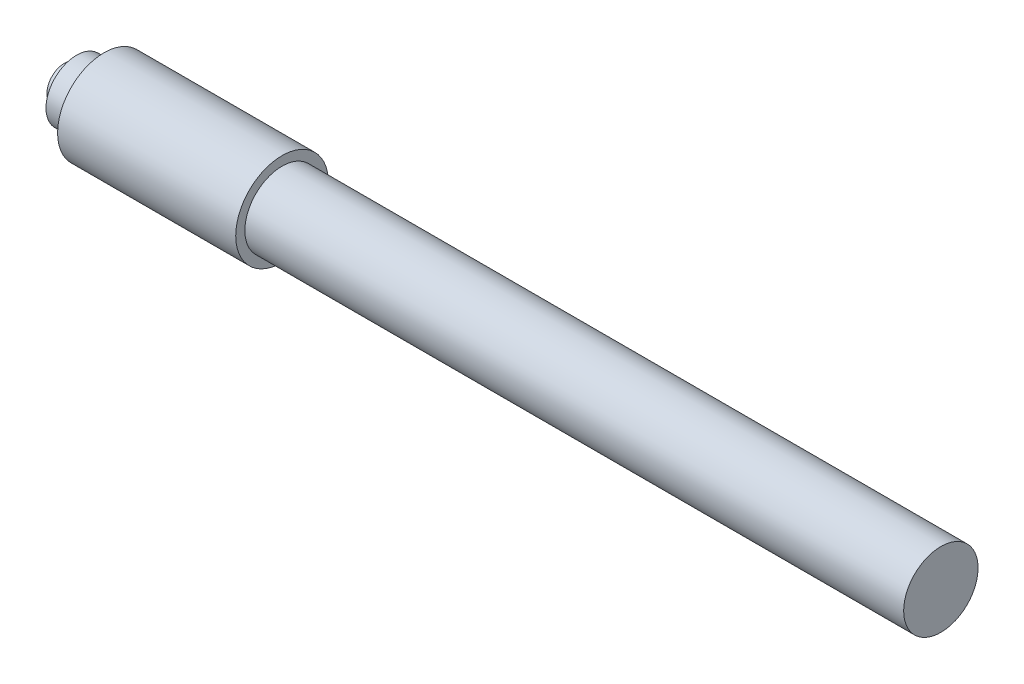
SolidWorks part; units mm, degrees
ref_plane "Plan de face" through (0, 0, 0) normal (0, 0, 1) x (1, 0, 0)
ref_plane "Plan de dessus" through (0, 0, 0) normal (0, 1, 0) x (1, 0, 0)
ref_plane "Plan de droite" through (0, 0, 0) normal (1, 0, 0) x (0, 0, -1)
sketch "Esquisse1" plane through (0, 0, 0) normal (0, 0, 1) x (1, 0, 0)
  line L0 (0, 0) -> (151.8444, 0) construction
  line L1 (0, 0) -> (0, 2.85)
  line L2 (0, 2.85) -> (2, 2.85)
  line L3 (2, 2.85) -> (2, 5)
  line L4 (2, 5) -> (6.5, 5)
  line L5 (6.5, 5) -> (6.5, 7.6)
  line L6 (6.5, 7.6) -> (35.7, 7.6)
  line L7 (35.7, 7.6) -> (35.7, 6.1)
  line L8 (35.7, 6.1) -> (143.7, 6.1)
  line L11 (143.7, 6.1) -> (143.7, 0)
  line L12 (0, 0) -> (143.7, 0)
  point P12 (0, 1.425)
  dimension "D1" = 2.85
  dimension "D2" = 6.5
  dimension "D3" = 29.2
  dimension "D4" = 15.2
  dimension "D5" = 12.2
  dimension "D6" = 108
  dimension "D9" = 5
  dimension "D10" = 2
revolve "Révolution1" add sketch "Esquisse1" angle 360 about L0
